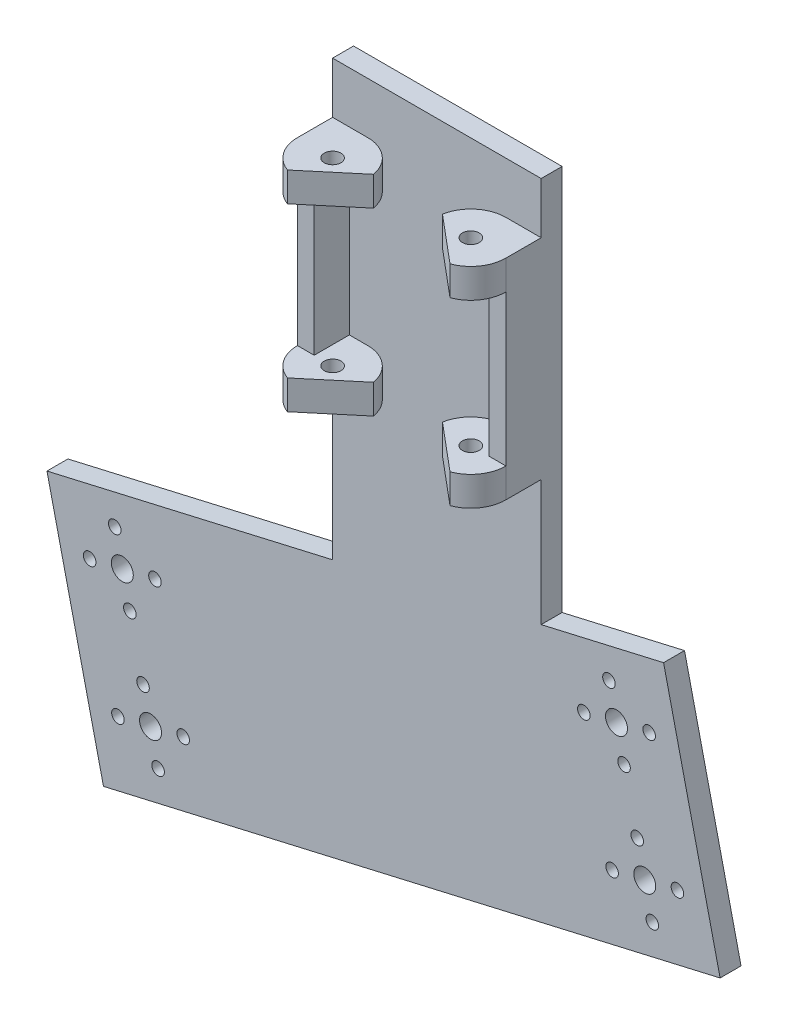
SolidWorks part; units mm, degrees
ref_plane "Front Plane" through (0, 0, 0) normal (0, 0, 1) x (1, 0, 0)
ref_plane "Top Plane" through (0, 0, 0) normal (0, 1, 0) x (1, 0, 0)
ref_plane "Right Plane" through (0, 0, 0) normal (1, 0, 0) x (0, 0, -1)
sketch "Sketch1" plane through (0, 0, 0) normal (0, 1, 0) x (1, 0, 0)
  line L0 (0, 22.8391) -> (0, -19.8342) construction
  line L1 (-35.1495, 0) -> (37.3645, 0) construction
  line L2 (-24.9, 0) -> (-24.9, 13.4)
  line L3 (-24.9, 13.4) -> (24.9, 13.4)
  line L4 (24.9, 0) -> (24.9, 13.4)
  line L5 (-19.4124, -7.879) -> (-8.235, 1.5)
  line L6 (19.4124, -7.879) -> (8.235, 1.5)
  line L7 (16.5, 8.4) -> (-16.5, 8.4)
  arc A0 (19.4124, -7.879) -> (24.9, 0) centre (16.5, 0) ccw
  arc A1 (-19.4124, -7.879) -> (-24.9, 0) centre (-16.5, 0) cw
  arc A2 (-16.5, 8.4) -> (-8.235, 1.5) centre (-16.5, 0) cw
  arc A3 (16.5, 8.4) -> (8.235, 1.5) centre (16.5, 0) ccw
  circle A4 centre (-16.5, 0) radius 8.4 construction
  circle A5 centre (16.5, 0) radius 8.4 construction
  point P14 (0, 13.4)
  dimension "D1" = 16.8
  dimension "D2" = 33
  dimension "D3" = 5
  dimension "D4" = 130
  dimension "D5" = 1.5
  dimension "D6" = 13.4
extrude "Boss-Extrude2" add sketch "Sketch1" along normal blind 7
sketch "Sketch3" plane through (0, 7, 0) normal (0, 1, 0) x (1, 0, 0)
  circle A0 centre (-16.5, 0) radius 2
  circle A1 centre (16.5, 0) radius 2
  dimension "D1" = 4
extrude "Cut-Extrude2" cut sketch "Sketch3" against normal through all both and the other way through all
sketch "Sketch4" plane through (0, 7, 0) normal (0, 1, 0) x (1, 0, 0)
  line L0 (-24.9, 13.4) -> (-24.9, 0)
  line L1 (-24.9, 13.4) -> (24.9, 13.4)
  line L2 (24.9, 13.4) -> (24.9, 0)
  line L3 (0, 13.4) -> (0, 0) construction
  line L4 (-16.5, 8.4) -> (16.5, 8.4)
  line L5 (-16.5, 8.4) -> (16.5, 8.4) construction
  line L6 (16.5, 8.4) -> (20.9, 8.4)
  line L7 (20.9, 8.4) -> (20.9, 0)
  line L8 (20.9, 0) -> (24.9, 0)
  line L9 (-20.9, 0) -> (-24.9, 0)
  line L10 (-20.9, 8.4) -> (-20.9, 0)
  line L11 (-16.5, 8.4) -> (-20.9, 8.4)
  circle A0 centre (-16.5, 0) radius 3.7 construction
  point P21 (0, 8.4)
  dimension "D2" = 7.4
  dimension "D1" = 4
extrude "Boss-Extrude3" add sketch "Sketch4" along normal blind 36
sketch "Sketch5" plane through (0, 43, 0) normal (0, 1, 0) x (1, 0, 0)
  line L12 (-24.9, 13.4) -> (-24.9, 0)
  line L13 (24.9, 13.4) -> (-24.9, 13.4)
  line L14 (24.9, 0) -> (24.9, 13.4)
  line L15 (8.235, 1.5) -> (19.4124, -7.879)
  line L16 (-16.5, 8.4) -> (16.5, 8.4)
  line L17 (-19.4124, -7.879) -> (-8.235, 1.5)
  line L18 (-24.9, 13.4) -> (-24.9, 0)
  line L19 (24.9, 13.4) -> (-24.9, 13.4)
  line L20 (24.9, 0) -> (24.9, 13.4)
  line L21 (8.235, 1.5) -> (19.4124, -7.879)
  line L22 (-16.5, 8.4) -> (16.5, 8.4)
  line L23 (-19.4124, -7.879) -> (-8.235, 1.5)
  circle A0 centre (-16.5, 0) radius 2 construction
  circle A1 centre (16.5, 0) radius 2
  circle A2 centre (16.5, 0) radius 2 construction
  circle A4 centre (-16.5, 0) radius 2
  arc A8 (-24.9, 0) -> (-19.4124, -7.879) centre (-16.5, 0) ccw
  arc A9 (19.4124, -7.879) -> (24.9, 0) centre (16.5, 0) ccw
  arc A10 (16.5, 8.4) -> (8.235, 1.5) centre (16.5, 0) ccw
  arc A11 (-8.235, 1.5) -> (-16.5, 8.4) centre (-16.5, 0) ccw
  arc A12 (-24.9, 0) -> (-19.4124, -7.879) centre (-16.5, 0) ccw
  arc A13 (19.4124, -7.879) -> (24.9, 0) centre (16.5, 0) ccw
  arc A14 (16.5, 8.4) -> (8.235, 1.5) centre (16.5, 0) ccw
  arc A15 (-8.235, 1.5) -> (-16.5, 8.4) centre (-16.5, 0) ccw
  dimension "D1" = 0
extrude "Boss-Extrude4" add sketch "Sketch5" along normal blind 7
sketch "Sketch13" plane through (0, 50, 0) normal (0, 1, 0) x (1, 0, 0)
  line L0 (24.9, 0) -> (24.9, 13.4) construction
  line L5 (-24.9, 13.4) -> (24.9, 13.4)
  line L6 (-24.9, 13.4) -> (-24.9, 8.4)
  line L7 (-24.9, 8.4) -> (24.9, 8.4)
  line L8 (24.9, 13.4) -> (24.9, 8.4)
  line L9 (-16.5, 8.4) -> (16.5, 8.4) construction
extrude "Boss-Extrude6" add sketch "Sketch13" along normal blind 12.25
sketch "Sketch15" plane through (0, 0, 0) normal (0, -1, 0) x (1, 0, 0)
  line L0 (24.9, 0) -> (24.9, -13.4) construction
  line L1 (-24.9, -13.4) -> (24.9, -13.4)
  line L2 (-24.9, -13.4) -> (-24.9, -8.4)
  line L3 (-24.9, -8.4) -> (24.9, -8.4)
  line L4 (24.9, -13.4) -> (24.9, -8.4)
  line L5 (-16.5, -8.4) -> (16.5, -8.4) construction
extrude "Boss-Extrude7" add sketch "Sketch15" along normal blind 30
sketch "Sketch12" plane through (0, 0, -13.4) normal (0, 0, -1) x (-1, 0, 0)
  line L11 (24.9, -30) -> (24.9, -41.4972)
  line L12 (-24.9, -30) -> (24.9, -30)
  line L14 (-24.9, -30) -> (-54.1311, -23.2515)
  line L15 (-54.1311, -23.2515) -> (-67.6282, -81.7137)
  line L16 (-67.6282, -81.7137) -> (79.6088, -115.706)
  line L17 (79.6088, -115.706) -> (93.1059, -57.2438)
  line L18 (93.1059, -57.2438) -> (24.9, -41.4972)
  dimension "D1" = 13
  dimension "D2" = 60
  dimension "D3" = 30
  dimension "D4" = 70
extrude "Boss-Extrude8" add sketch "Sketch12" against normal blind 5
sketch "Sketch16" plane through (0, 0, -8.4) normal (0, 0, 1) x (1, 0, 0)
  line L0 (60.8796, -52.4826) -> (-86.3574, -86.4749) construction
  line L1 (54.1311, -23.2515) -> (67.6282, -81.7137) construction
  line L2 (-79.6088, -115.706) -> (-93.1059, -57.2438) construction
  line L3 (-75.1161, -68.4851) -> (-82.911, -70.2847) construction
  line L4 (-93.1059, -57.2438) -> (-24.9, -41.4972) construction
  line L6 (42.8898, -41.2413) -> (50.6848, -39.4417) construction
  line L7 (42.8898, -41.2413) -> (35.0949, -43.0409) construction
  line L8 (24.9, -30) -> (54.1311, -23.2515) construction
  line L9 (42.8898, -41.2413) -> (44.6894, -49.0362) construction
  line L10 (42.8898, -41.2413) -> (41.0902, -33.4463) construction
  circle A0 centre (42.8898, -41.2413) radius 8 construction
  circle A1 centre (42.8898, -41.2413) radius 2.625
  circle A2 centre (50.6848, -39.4417) radius 1.5
  circle A3 centre (44.6894, -49.0362) radius 1.5
  circle A4 centre (35.0949, -43.0409) radius 1.5
  circle A5 centre (41.0902, -33.4463) radius 1.5
  circle A21 centre (-75.1161, -68.4851) radius 8 construction
  circle A22 centre (-82.911, -70.2847) radius 1.5
  circle A23 centre (-76.9157, -60.6901) radius 1.5
  circle A24 centre (-67.3211, -66.6855) radius 1.5
  circle A25 centre (-73.3165, -76.2801) radius 1.5
  circle A26 centre (-75.1161, -68.4851) radius 2.625
  circle A27 centre (47.8387, -62.6774) radius 1.5
  circle A28 centre (57.4333, -68.6728) radius 1.5
  circle A29 centre (51.438, -78.2673) radius 1.5
  circle A30 centre (49.6383, -70.4724) radius 2.625
  circle A31 centre (41.8434, -72.272) radius 1.5
  circle A32 centre (-70.1672, -89.9212) radius 1.5
  circle A33 centre (-68.3676, -97.7162) radius 2.625
  circle A34 centre (-76.1625, -99.5158) radius 1.5
  circle A35 centre (-66.5679, -105.5112) radius 1.5
  circle A36 centre (-60.5726, -95.9166) radius 1.5
  point P33 (42.8898, -41.2413)
  point P37 (-75.1161, -68.4851)
  dimension "D1" = 16
  dimension "D4" = 5.25
  dimension "D5" = 3
  dimension "D2" = 15
  dimension "D3" = 15
  dimension "D7" = 15
  dimension "D8" = 15
  dimension "D6" = 4
  dimension "D9" = 4
extrude "Cut-Extrude3" cut sketch "Sketch16" against normal through all both and the other way through all
